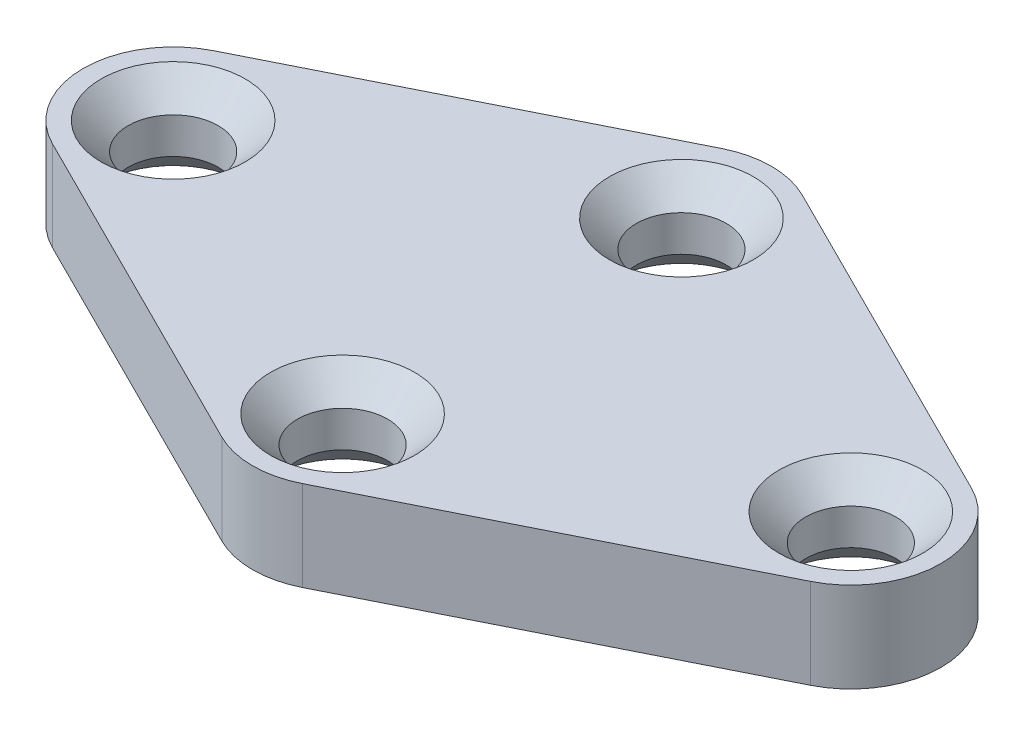
SolidWorks part; units mm, degrees
ref_plane "Front Plane" through (0, 0, 0) normal (0, 0, 1) x (1, 0, 0)
ref_plane "Top Plane" through (0, 0, 0) normal (0, 1, 0) x (1, 0, 0)
ref_plane "Right Plane" through (0, 0, 0) normal (1, 0, 0) x (0, 0, -1)
sketch "Sketch1" plane through (0, 0, 0) normal (0, 1, 0) x (1, 0, 0)
  line L0 (-4.4721, 27.7639) -> (-42.1115, 8.9443)
  line L5 (30, -15) -> (-30, 15) construction
  line L6 (30, 15) -> (-30, -15) construction
  line L7 (-42.1115, -8.9443) -> (-4.4721, -27.7639)
  line L8 (4.4721, -27.7639) -> (42.1115, -8.9443)
  line L9 (42.1115, 8.9443) -> (4.4721, 27.7639)
  arc A0 (-4.4721, -27.7639) -> (4.4721, -27.7639) centre (0, -18.8197) ccw
  arc A1 (-42.1115, 8.9443) -> (-42.1115, -8.9443) centre (-37.6393, 0) ccw
  arc A2 (-4.4721, 27.7639) -> (4.4721, 27.7639) centre (0, 18.8197) cw
  arc A3 (42.1115, -8.9443) -> (42.1115, 8.9443) centre (37.6393, 0) ccw
  circle A4 centre (0, 18.8197) radius 5
  circle A5 centre (37.6393, 0) radius 5
  circle A6 centre (0, -18.8197) radius 5
  circle A7 centre (-37.6393, 0) radius 5
  point P0 (0, 0)
  point P12 (0, -30)
  point P15 (-60, 0)
  point P18 (0, 30)
  point P21 (60, 0)
  point P26 (0, 0)
  point P27 (0, 0)
  point P28 (0, 0)
  dimension "D3" = 10
  dimension "D4" = 10
  dimension "D5" = 10
  dimension "D6" = 10
  dimension "D7" = 10
  dimension "D1" = 120
  dimension "D2" = 60
  dimension "D8" = 60
  dimension "D9" = 30
extrude "Boss-Extrude1" add sketch "Sketch1" along normal blind 10 contours L9 A2 L0 A1 L7 A0 L8 A3
chamfer "Chamfer1" distance 3 angle 45 8 edges at (0, 0, 23.8197) (0, 10, 23.8197) (37.6393, 0, 5) (37.6393, 10, 5) (0, 0, -13.8197) (0, 10, -13.8197) (-37.6393, 0, 5) (-37.6393, 10, 5)
